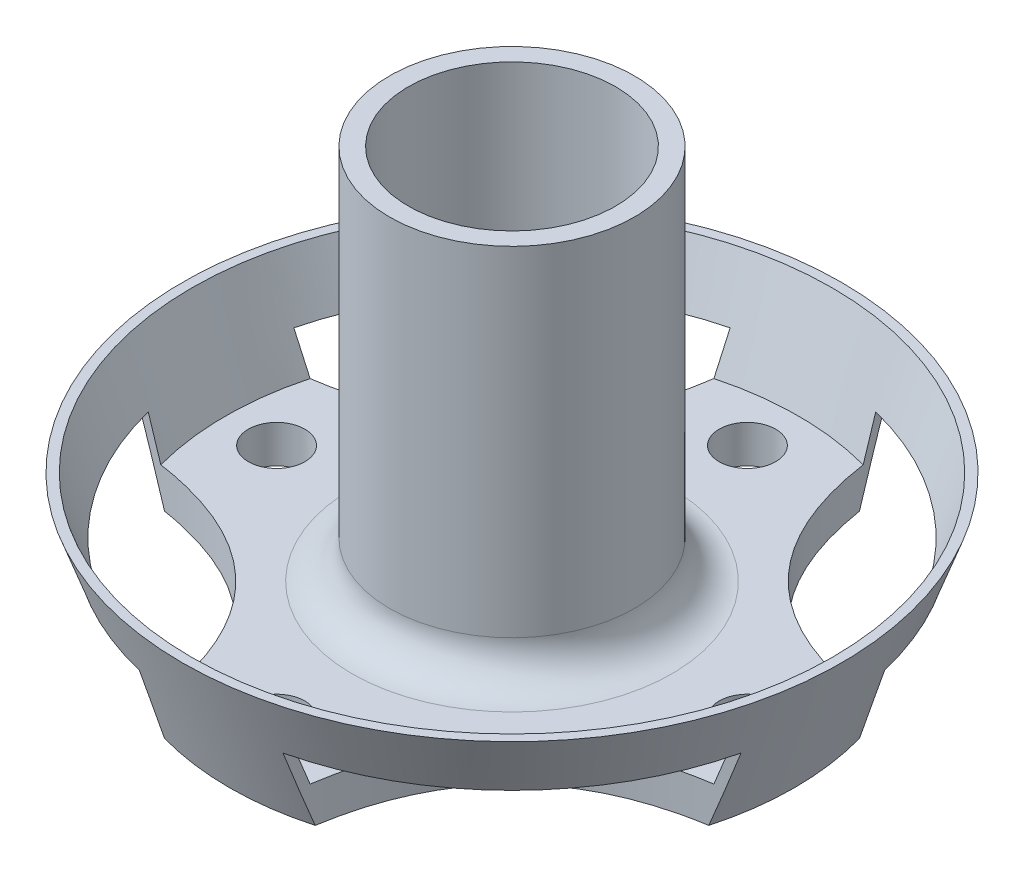
SolidWorks part; units mm, degrees
ref_plane "Front Plane" through (0, 0, 0) normal (0, 0, 1) x (1, 0, 0)
ref_plane "Top Plane" through (0, 0, 0) normal (0, 1, 0) x (1, 0, 0)
ref_plane "Right Plane" through (0, 0, 0) normal (1, 0, 0) x (0, 0, -1)
sketch "Sketch1" plane through (0, 0, 0) normal (0, 1, 0) x (1, 0, 0)
  circle A0 centre (0, 0) radius 17.5
  dimension "D1" = 35
extrude "Boss-Extrude1" add sketch "Sketch1" against normal blind 7 draft 19.7
sketch "Sketch4" plane through (0, -7, 0) normal (0, -1, 0) x (1, 0, 0)
  circle A1 centre (0, 0) radius 14.9936
  circle A2 centre (0, 0) radius 14.9936
  dimension "D1" = 0
sketch "Sketch5" plane through (0, 0, 0) normal (0, 1, 0) x (1, 0, 0)
  circle A0 centre (0, 0) radius 17
  dimension "D1" = 34
extrude "Cut-Extrude1" cut sketch "Sketch5" against normal blind 5 draft 19.7
sketch "Sketch6" plane through (0, -7, 0) normal (0, -1, 0) x (1, 0, 0)
  line L0 (0, 0) -> (0, 17.5) construction
  line L1 (0, 0) -> (17.5, 0) construction
  line L2 (0, 0) -> (10.6021, 10.6021) construction
  line L3 (3.7458, 17.0944) -> (4.2463, 4.2463) construction
  line L4 (4.2463, 4.2463) -> (17.0944, 3.7458) construction
  line L5 (-3.7458, 17.0944) -> (-4.2463, 4.2463) construction
  line L6 (-4.2463, 4.2463) -> (-17.0944, 3.7458) construction
  line L7 (3.7458, -17.0944) -> (4.2463, -4.2463) construction
  line L8 (4.2463, -4.2463) -> (17.0944, -3.7458) construction
  line L9 (-3.7458, -17.0944) -> (-4.2463, -4.2463) construction
  line L10 (-4.2463, -4.2463) -> (-17.0944, -3.7458) construction
  circle A0 centre (0, 0) radius 14.9936 construction
  circle A1 centre (0, 0) radius 17.5 construction
  circle A2 centre (0, 0) radius 17.5
  circle A3 centre (0, 0) radius 14.9936
  spline S0 degree 2 poles (3.7458, 17.0944) (4.2463, 4.2463) (17.0944, 3.7458) knots 0 0 0 1 1 1
  spline S1 degree 2 poles (-3.7458, 17.0944) (-4.2463, 4.2463) (-17.0944, 3.7458) knots 0 0 0 1 1 1
  spline S2 degree 2 poles (3.7458, -17.0944) (4.2463, -4.2463) (17.0944, -3.7458) knots 0 0 0 1 1 1
  spline S3 degree 2 poles (-3.7458, -17.0944) (-4.2463, -4.2463) (-17.0944, -3.7458) knots 0 0 0 1 1 1
  point P3 (4, 14.4502)
  point P14 (14.4502, 4)
  circle M6 centre (0, 0) radius 14.9936
  dimension "D1" = 4
  dimension "D2" = 4
  dimension "D3" = 45
extrude "Cut-Extrude2" cut sketch "Sketch6" against normal blind 4 contours S1 A2 M6 | S1 M6 | A2 S3 M6 | S3 M6 | S2 M6 | S2 A2 M6 | S0 M6 | A2 S0 M6
sketch "Sketch7" plane through (0, -7, 0) normal (0, -1, 0) x (1, 0, 0)
  circle A0 centre (0, 0) radius 5.5
  dimension "D1" = 11
extrude "Cut-Extrude3" cut sketch "Sketch7" against normal through all
sketch "Sketch8" plane through (0, -7, 0) normal (0, -1, 0) x (1, 0, 0)
  circle A0 centre (-12.5, 0) radius 1.5
  circle A1 centre (0, 12.5) radius 1.5
  circle A2 centre (12.5, 0) radius 1.5
  circle A3 centre (0, -12.5) radius 1.5
  dimension "D4" = 3
  dimension "D5" = 3
  dimension "D6" = 3
  dimension "D7" = 3
  dimension "D1" = 12.5
  dimension "D2" = 12.5
  dimension "D3" = 12.5
  dimension "D8" = 12.5
extrude "Cut-Extrude4" cut sketch "Sketch8" against normal through all
sketch "Sketch9" plane through (0, -5, 0) normal (0, 1, 0) x (1, 0, 0)
  circle A0 centre (0, 0) radius 6.5
  dimension "D1" = 13
extrude "Boss-Extrude2" add sketch "Sketch9" along normal blind 20
fillet "Fillet1" radius 2 1 edges at (0, -5, 6.5)
sketch "Sketch10" plane through (0, -5, 0) normal (0, -1, 0) x (1, 0, 0)
  circle A1 centre (0, 0) radius 5.5
  circle A2 centre (0, 0) radius 5.5
  dimension "D1" = 0
extrude "Cut-Extrude5" cut sketch "Sketch10" against normal through all
